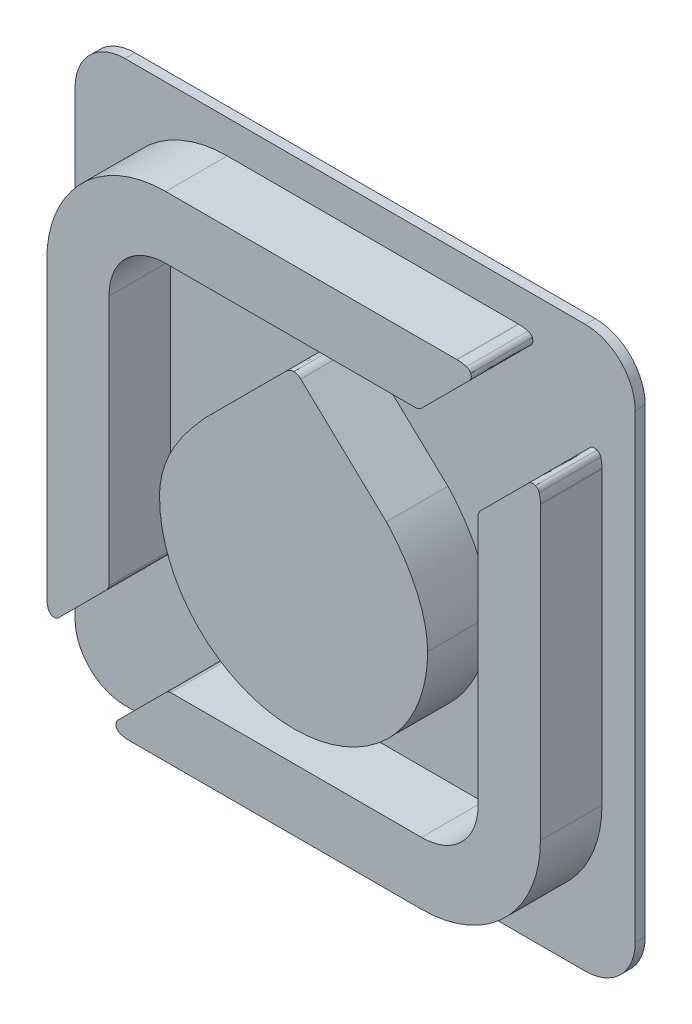
SolidWorks part; units mm, degrees
ref_plane "Front Plane" through (0, 0, 0) normal (0, 0, 1) x (1, 0, 0)
ref_plane "Top Plane" through (0, 0, 0) normal (0, 1, 0) x (1, 0, 0)
ref_plane "Right Plane" through (0, 0, 0) normal (1, 0, 0) x (0, 0, -1)
sketch "Sketch1" plane through (0, 0, 0) normal (0, 0, 1) x (1, 0, 0)
  line L0 (-0.4439, 10.3739) -> (-5.2973, 5.5207)
  line L1 (5.5576, 5.5207) -> (0.4078, 10.3739)
  line L2 (-7.7061, 12.3406) -> (7.3726, 12.3406)
  line L3 (7.6331, 12.4506) -> (10.56, 15.3777)
  line L4 (9.7814, 16.0818) -> (-7.7061, 16.0818)
  line L5 (-14.8551, 8.9323) -> (-14.8537, -8.5549)
  line L6 (-14.1496, -9.3319) -> (-11.224, -6.405)
  line L7 (-11.1125, -6.1461) -> (-11.1139, 8.9323)
  line L8 (7.67, -9.8545) -> (-7.4083, -9.8545)
  line L9 (-7.6688, -9.966) -> (-10.5958, -12.8929)
  line L10 (-9.8171, -13.5971) -> (7.67, -13.5971)
  line L11 (14.8194, -6.4463) -> (14.818, 11.0395)
  line L12 (14.1139, 11.8167) -> (11.1869, 8.8897)
  line L13 (11.0768, 8.6308) -> (11.0779, -6.4463)
  line L14 (-8.0765, 0) -> (8.0395, 0) construction
  line L15 (0, 10.5587) -> (0, -8.0393) construction
  spline S0 degree 3 poles (0, 10.5587) (-0.1504, 10.5587) (-0.3295, 10.487) (-0.4439, 10.3739) knots 0 0 0 0 1 1 1 1
  spline S1 degree 3 poles (-5.2973, 5.5207) (-5.3111, 5.508) (-5.3235, 5.4956) (-5.3344, 5.4832) knots 0 0 0 0 1 1 1 1
  spline S2 degree 3 poles (-5.3344, 5.4832) (-6.6213, 4.0569) (-8.0765, 2.26) (-8.0765, 0) knots 0 0 0 0 1 1 1 1
  spline S3 degree 3 poles (-8.0765, 0) (-8.0765, -4.44) (-4.4387, -8.0393) (0, -8.0393) knots 0 0 0 0 1 1 1 1
  spline S4 degree 3 poles (0, -8.0393) (4.4414, -8.0393) (8.0395, -4.44) (8.0395, 0) knots 0 0 0 0 1 1 1 1
  spline S5 degree 3 poles (8.0395, 0) (8.0395, 2.1015) (6.8156, 4.1908) (5.5576, 5.5207) knots 0 0 0 0 1 1 1 1
  spline S6 degree 3 poles (0.4078, 10.3739) (0.2949, 10.4829) (0.1545, 10.5587) (0, 10.5587) knots 0 0 0 0 1 1 1 1
  spline S7 degree 3 poles (7.3726, 12.3406) (7.44, 12.3472) (7.5049, 12.3734) (7.5585, 12.4136) knots 0 0 0 0 1 1 1 1
  spline S8 degree 3 poles (7.5585, 12.4136) (7.5847, 12.4245) (7.6094, 12.4354) (7.6331, 12.4506) knots 0 0 0 0 1 1 1 1
  spline S9 degree 3 poles (10.56, 15.3777) (10.6605, 15.4838) (10.691, 15.6504) (10.6331, 15.7854) knots 0 0 0 0 1 1 1 1
  spline S10 degree 3 poles (10.6331, 15.7854) (10.589, 15.8944) (10.4895, 15.9799) (10.3737, 16.0073) knots 0 0 0 0 1 1 1 1
  spline S11 degree 3 poles (10.3737, 16.0073) (10.1974, 16.0529) (10.0087, 16.0914) (9.8185, 16.0818) knots 0 0 0 0 1 1 1 1
  spline S12 degree 3 poles (9.8185, 16.0818) (9.8061, 16.0818) (9.7939, 16.0832) (9.7814, 16.0818) knots 0 0 0 0 1 1 1 1
  spline S13 degree 3 poles (-7.7061, 16.0818) (-11.6308, 16.0818) (-14.8551, 12.8585) (-14.8551, 8.9323) knots 0 0 0 0 1 1 1 1
  spline S14 degree 3 poles (-14.8537, -8.5549) (-14.8551, -8.5671) (-14.8537, -8.5781) (-14.8537, -8.5904) knots 0 0 0 0 1 1 1 1
  spline S15 degree 3 poles (-14.8537, -8.5904) (-14.8637, -8.782) (-14.8248, -8.9697) (-14.7807, -9.1476) knots 0 0 0 0 1 1 1 1
  spline S16 degree 3 poles (-14.7807, -9.1476) (-14.7518, -9.2618) (-14.6678, -9.3609) (-14.5577, -9.4064) knots 0 0 0 0 1 1 1 1
  spline S17 degree 3 poles (-14.5577, -9.4064) (-14.4241, -9.4642) (-14.2558, -9.4339) (-14.1496, -9.3319) knots 0 0 0 0 1 1 1 1
  spline S18 degree 3 poles (-11.224, -6.405) (-11.2088, -6.3817) (-11.1966, -6.3566) (-11.1869, -6.3306) knots 0 0 0 0 1 1 1 1
  spline S19 degree 3 poles (-11.1869, -6.3306) (-11.1457, -6.2784) (-11.1192, -6.2134) (-11.1125, -6.1461) knots 0 0 0 0 1 1 1 1
  spline S20 degree 3 poles (-11.1139, 8.9323) (-11.1139, 10.8565) (-9.6326, 12.3406) (-7.7061, 12.3406) knots 0 0 0 0 1 1 1 1
  spline S21 degree 3 poles (-7.4083, -9.8545) (-7.4757, -9.8626) (-7.5406, -9.8887) (-7.5942, -9.9285) knots 0 0 0 0 1 1 1 1
  spline S22 degree 3 poles (-7.5942, -9.9285) (-7.6204, -9.9384) (-7.6455, -9.9508) (-7.6688, -9.966) knots 0 0 0 0 1 1 1 1
  spline S23 degree 3 poles (-10.5958, -12.8929) (-10.6962, -12.9992) (-10.7267, -13.1656) (-10.6688, -13.3007) knots 0 0 0 0 1 1 1 1
  spline S24 degree 3 poles (-10.6688, -13.3007) (-10.6247, -13.4097) (-10.5241, -13.4951) (-10.4098, -13.5227) knots 0 0 0 0 1 1 1 1
  spline S25 degree 3 poles (-10.4098, -13.5227) (-10.2334, -13.5682) (-10.0447, -13.6066) (-9.8545, -13.5971) knots 0 0 0 0 1 1 1 1
  spline S26 degree 3 poles (-9.8545, -13.5971) (-9.8418, -13.5956) (-9.8296, -13.5971) (-9.8171, -13.5971) knots 0 0 0 0 1 1 1 1
  spline S27 degree 3 poles (7.67, -13.5971) (11.5947, -13.5971) (14.8209, -10.3724) (14.8194, -6.4463) knots 0 0 0 0 1 1 1 1
  spline S28 degree 3 poles (14.818, 11.0395) (14.8194, 11.0519) (14.818, 11.0643) (14.818, 11.0769) knots 0 0 0 0 1 1 1 1
  spline S29 degree 3 poles (14.818, 11.0769) (14.8276, 11.2671) (14.7891, 11.4558) (14.7436, 11.6321) knots 0 0 0 0 1 1 1 1
  spline S30 degree 3 poles (14.7436, 11.6321) (14.7161, 11.7465) (14.6308, 11.847) (14.5218, 11.8911) knots 0 0 0 0 1 1 1 1
  spline S31 degree 3 poles (14.5218, 11.8911) (14.3866, 11.949) (14.2201, 11.9186) (14.1139, 11.8167) knots 0 0 0 0 1 1 1 1
  spline S32 degree 3 poles (11.1869, 8.8897) (11.1718, 8.8678) (11.1593, 8.8418) (11.1499, 8.8167) knots 0 0 0 0 1 1 1 1
  spline S33 degree 3 poles (11.1499, 8.8167) (11.1096, 8.7631) (11.0836, 8.6982) (11.0768, 8.6308) knots 0 0 0 0 1 1 1 1
  spline S34 degree 3 poles (11.0779, -6.4463) (11.0793, -8.3713) (9.5965, -9.8545) (7.67, -9.8545) knots 0 0 0 0 1 1 1 1
extrude "Boss-Extrude1" add sketch "Sketch1" along normal blind 3.7
sketch "Sketch2" plane through (0, 0, 0) normal (0, 0, 1) x (1, 0, 0)
  line L0 (-14.8551, 8.9323) -> (-16.8551, 8.9323) construction
  line L1 (-16.8551, 18.0778) -> (16.8194, 18.0778)
  line L2 (-16.8551, 18.0778) -> (-16.8551, -15.5971)
  line L3 (-16.8551, -15.5971) -> (16.8194, -15.5971)
  line L4 (16.8194, 18.0778) -> (16.8194, -15.5971)
  line L5 (-7.9473, 16.0778) -> (-7.9473, 18.0778) construction
  line L6 (14.8194, -6.4463) -> (16.8194, -6.4463) construction
  line L7 (7.67, -13.5971) -> (7.67, -15.5971) construction
  spline S0 degree 3 poles (-7.7061, 16.0818) (-11.6308, 16.0818) (-14.8551, 12.8585) (-14.8551, 8.9323) knots 0 0 0 0 1 1 1 1 construction
  point P0 (0, 0)
  dimension "D1" = 2
extrude "Boss-Extrude2" add sketch "Sketch2" against normal blind 0.6
fillet "Fillet1" radius 3 4 edges at (-16.8551, -15.5971, -0.3) (16.8194, -15.5971, -0.3) (-16.8551, 18.0778, -0.3) (16.8194, 18.0778, -0.3)
sketch "Sketch3" plane through (0, 0, 0) normal (0, 0, 1) x (1, 0, 0)
  line L0 (-0.4439, 10.3744) -> (-5.2976, 5.521)
  line L1 (5.5579, 5.521) -> (0.4078, 10.3744)
  line L2 (-7.7065, 12.3412) -> (7.373, 12.3412)
  line L3 (7.6335, 12.4512) -> (10.5606, 15.3784)
  line L4 (9.7819, 16.0826) -> (-7.7065, 16.0826)
  line L5 (-14.8558, 8.9327) -> (-14.8545, -8.5553)
  line L6 (-14.1503, -9.3324) -> (-11.2245, -6.4053)
  line L7 (-11.113, -6.1464) -> (-11.1144, 8.9327)
  line L8 (7.6704, -9.855) -> (-7.4087, -9.855)
  line L9 (-7.6692, -9.9665) -> (-10.5963, -12.8936)
  line L10 (-9.8176, -13.5978) -> (7.6704, -13.5978)
  line L11 (14.8201, -6.4467) -> (14.8188, 11.04)
  line L12 (14.1146, 11.8173) -> (11.1874, 8.8902)
  line L13 (11.0773, 8.6312) -> (11.0784, -6.4467)
  line L14 (29.3977, 1.1866) -> (27.6725, 1.1866)
  line L15 (27.6725, 1.1866) -> (27.6725, 6.5529)
  line L16 (27.6725, -3.5649) -> (27.6725, 0.3487)
  line L17 (31.1507, -0.5676) -> (34.1272, -4.7585)
  line L18 (36.2856, -4.3009) -> (32.8307, 0.7829)
  line L19 (25.3049, 5.8184) -> (25.3049, -3.5649)
  line L20 (50.1342, 0.962) -> (43.1704, 0.8573)
  line L21 (43.0424, -0.1845) -> (52.5774, -0.1845)
  line L22 (59.4392, -3.0798) -> (59.4392, 0.9317)
  line L23 (57.2258, 2.3331) -> (57.2258, -9.36)
  line L24 (59.4392, -9.36) -> (59.4392, -5.4475)
  line L25 (77.8244, 1.1866) -> (76.0989, 1.1866)
  line L26 (76.0989, 1.1866) -> (76.0989, 6.5529)
  line L27 (76.0989, -3.5649) -> (76.0989, 0.3487)
  line L28 (79.5775, -0.5676) -> (82.5526, -4.7585)
  line L29 (84.712, -4.3009) -> (81.2557, 0.7829)
  line L30 (73.7313, 5.8184) -> (73.7313, -3.5649)
  line L31 (97.9983, -0.3128) -> (97.8247, -3.7166)
  line L32 (94.9473, -0.8972) -> (97.9983, -0.3128)
  line L33 (100.0367, -3.0798) -> (100.2103, 1.0143)
  line L34 (97.7958, 0.6022) -> (94.4912, 0.0456)
  line L35 (97.0323, -5.7481) -> (97.7436, -5.2673)
  line L36 (97.7436, -5.2673) -> (97.8247, -5.2673)
  line L37 (108.3507, -3.0798) -> (108.3507, 0.9317)
  line L38 (106.139, 2.3331) -> (106.139, -9.36)
  line L39 (108.3507, -9.36) -> (108.3507, -5.4475)
  line L40 (125.015, 1.0143) -> (125.015, 6.5529)
  line L41 (122.6527, 5.8184) -> (122.6527, -3.5649)
  line L42 (125.015, -3.5649) -> (125.015, 0.2205)
  line L43 (139.923, 2.6873) -> (139.923, -3.4615)
  line L44 (142.1337, -3.4615) -> (142.1337, 0.0456)
  spline S0 degree 3 poles (0, 10.5592) (-0.1504, 10.5592) (-0.3295, 10.4875) (-0.4439, 10.3744) knots 0 0 0 0 1 1 1 1
  spline S1 degree 3 poles (-5.2976, 5.521) (-5.3114, 5.5083) (-5.3237, 5.4959) (-5.3346, 5.4835) knots 0 0 0 0 1 1 1 1
  spline S2 degree 3 poles (-5.3346, 5.4835) (-6.6216, 4.0571) (-8.0769, 2.2601) (-8.0769, 0) knots 0 0 0 0 1 1 1 1
  spline S3 degree 3 poles (-8.0769, 0) (-8.0769, -4.4402) (-4.4389, -8.0397) (0, -8.0397) knots 0 0 0 0 1 1 1 1
  spline S4 degree 3 poles (0, -8.0397) (4.4416, -8.0397) (8.0399, -4.4402) (8.0399, 0) knots 0 0 0 0 1 1 1 1
  spline S5 degree 3 poles (8.0399, 0) (8.0399, 2.1016) (6.816, 4.191) (5.5579, 5.521) knots 0 0 0 0 1 1 1 1
  spline S6 degree 3 poles (0.4078, 10.3744) (0.2949, 10.4834) (0.1545, 10.5592) (0, 10.5592) knots 0 0 0 0 1 1 1 1
  spline S7 degree 3 poles (7.373, 12.3412) (7.4404, 12.3478) (7.5053, 12.374) (7.5589, 12.4143) knots 0 0 0 0 1 1 1 1
  spline S8 degree 3 poles (7.5589, 12.4143) (7.5851, 12.4251) (7.6098, 12.436) (7.6335, 12.4512) knots 0 0 0 0 1 1 1 1
  spline S9 degree 3 poles (10.5606, 15.3784) (10.661, 15.4845) (10.6915, 15.6511) (10.6336, 15.7862) knots 0 0 0 0 1 1 1 1
  spline S10 degree 3 poles (10.6336, 15.7862) (10.5895, 15.8952) (10.49, 15.9807) (10.3743, 16.0081) knots 0 0 0 0 1 1 1 1
  spline S11 degree 3 poles (10.3743, 16.0081) (10.1979, 16.0537) (10.0092, 16.0921) (9.819, 16.0826) knots 0 0 0 0 1 1 1 1
  spline S12 degree 3 poles (9.819, 16.0826) (9.8066, 16.0826) (9.7943, 16.084) (9.7819, 16.0826) knots 0 0 0 0 1 1 1 1
  spline S13 degree 3 poles (-7.7065, 16.0826) (-11.6314, 16.0826) (-14.8558, 12.8591) (-14.8558, 8.9327) knots 0 0 0 0 1 1 1 1
  spline S14 degree 3 poles (-14.8545, -8.5553) (-14.8558, -8.5676) (-14.8545, -8.5786) (-14.8545, -8.5908) knots 0 0 0 0 1 1 1 1
  spline S15 degree 3 poles (-14.8545, -8.5908) (-14.8644, -8.7824) (-14.8255, -8.9701) (-14.7814, -9.148) knots 0 0 0 0 1 1 1 1
  spline S16 degree 3 poles (-14.7814, -9.148) (-14.7525, -9.2622) (-14.6686, -9.3613) (-14.5584, -9.4068) knots 0 0 0 0 1 1 1 1
  spline S17 degree 3 poles (-14.5584, -9.4068) (-14.4248, -9.4647) (-14.2565, -9.4344) (-14.1503, -9.3324) knots 0 0 0 0 1 1 1 1
  spline S18 degree 3 poles (-11.2245, -6.4053) (-11.2094, -6.382) (-11.1971, -6.3569) (-11.1874, -6.3309) knots 0 0 0 0 1 1 1 1
  spline S19 degree 3 poles (-11.1874, -6.3309) (-11.1462, -6.2787) (-11.1198, -6.2137) (-11.113, -6.1464) knots 0 0 0 0 1 1 1 1
  spline S20 degree 3 poles (-11.1144, 8.9327) (-11.1144, 10.857) (-9.6331, 12.3412) (-7.7065, 12.3412) knots 0 0 0 0 1 1 1 1
  spline S21 degree 3 poles (-7.4087, -9.855) (-7.4761, -9.8631) (-7.541, -9.8892) (-7.5946, -9.929) knots 0 0 0 0 1 1 1 1
  spline S22 degree 3 poles (-7.5946, -9.929) (-7.6208, -9.9389) (-7.6459, -9.9513) (-7.6692, -9.9665) knots 0 0 0 0 1 1 1 1
  spline S23 degree 3 poles (-10.5963, -12.8936) (-10.6967, -12.9998) (-10.7272, -13.1663) (-10.6693, -13.3013) knots 0 0 0 0 1 1 1 1
  spline S24 degree 3 poles (-10.6693, -13.3013) (-10.6252, -13.4103) (-10.5246, -13.4958) (-10.4103, -13.5234) knots 0 0 0 0 1 1 1 1
  spline S25 degree 3 poles (-10.4103, -13.5234) (-10.2339, -13.5688) (-10.0452, -13.6073) (-9.855, -13.5978) knots 0 0 0 0 1 1 1 1
  spline S26 degree 3 poles (-9.855, -13.5978) (-9.8423, -13.5963) (-9.83, -13.5978) (-9.8176, -13.5978) knots 0 0 0 0 1 1 1 1
  spline S27 degree 3 poles (7.6704, -13.5978) (11.5952, -13.5978) (14.8217, -10.3729) (14.8201, -6.4467) knots 0 0 0 0 1 1 1 1
  spline S28 degree 3 poles (14.8188, 11.04) (14.8201, 11.0524) (14.8188, 11.0648) (14.8188, 11.0775) knots 0 0 0 0 1 1 1 1
  spline S29 degree 3 poles (14.8188, 11.0775) (14.8283, 11.2677) (14.7898, 11.4563) (14.7444, 11.6327) knots 0 0 0 0 1 1 1 1
  spline S30 degree 3 poles (14.7444, 11.6327) (14.7168, 11.7471) (14.6315, 11.8476) (14.5225, 11.8917) knots 0 0 0 0 1 1 1 1
  spline S31 degree 3 poles (14.5225, 11.8917) (14.3873, 11.9496) (14.2208, 11.9192) (14.1146, 11.8173) knots 0 0 0 0 1 1 1 1
  spline S32 degree 3 poles (11.1874, 8.8902) (11.1723, 8.8682) (11.1599, 8.8422) (11.1504, 8.8171) knots 0 0 0 0 1 1 1 1
  spline S33 degree 3 poles (11.1504, 8.8171) (11.1101, 8.7635) (11.0841, 8.6986) (11.0773, 8.6312) knots 0 0 0 0 1 1 1 1
  spline S34 degree 3 poles (11.0784, -6.4467) (11.0798, -8.3717) (9.597, -9.855) (7.6704, -9.855) knots 0 0 0 0 1 1 1 1
  spline S35 degree 3 poles (30.2881, 8.0304) (31.8397, 8.0304) (33.9247, 7.723) (33.9247, 4.8742) knots 0 0 0 0 1 1 1 1
  spline S36 degree 3 poles (33.9247, 4.8742) (33.9247, 1.8522) (31.8644, 1.1866) (29.3977, 1.1866) knots 0 0 0 0 1 1 1 1
  spline S37 degree 3 poles (27.6725, 6.5529) (27.6725, 7.2669) (28.4839, 8.0304) (30.2881, 8.0304) knots 0 0 0 0 1 1 1 1
  spline S38 degree 3 poles (27.6725, 0.3487) (29.8083, 0.3487) (30.7704, -0.0056) (31.1507, -0.5676) knots 0 0 0 0 1 1 1 1
  spline S39 degree 3 poles (34.1272, -4.7585) (34.8618, -5.8761) (35.9575, -6.918) (37.4844, -6.918) knots 0 0 0 0 1 1 1 1
  spline S40 degree 3 poles (37.4844, -6.918) (37.8676, -6.918) (38.2962, -6.871) (38.5513, -6.7443) knots 0 0 0 0 1 1 1 1
  spline S41 degree 3 poles (38.5513, -6.7443) (38.6243, -6.5636) (38.6243, -6.2565) (38.5262, -6.0553) knots 0 0 0 0 1 1 1 1
  spline S42 degree 3 poles (38.5262, -6.0553) (37.5314, -5.9795) (36.9471, -5.3427) (36.2856, -4.3009) knots 0 0 0 0 1 1 1 1
  spline S43 degree 3 poles (32.8307, 0.7829) (33.9247, 1.112) (36.4659, 2.3567) (36.4659, 4.8979) knots 0 0 0 0 1 1 1 1
  spline S44 degree 3 poles (36.4659, 4.8979) (36.4659, 6.1189) (36.0609, 7.1608) (35.1472, 7.9779) knots 0 0 0 0 1 1 1 1
  spline S45 degree 3 poles (35.1472, 7.9779) (33.9247, 9.0722) (31.8644, 9.0722) (30.2659, 9.0722) knots 0 0 0 0 1 1 1 1
  spline S46 degree 3 poles (30.2659, 9.0722) (29.6291, 9.0722) (27.4421, 8.9166) (26.4733, 8.9166) knots 0 0 0 0 1 1 1 1
  spline S47 degree 3 poles (26.4733, 8.9166) (25.5363, 8.9166) (24.292, 8.944) (23.1976, 8.9673) knots 0 0 0 0 1 1 1 1
  spline S48 degree 3 poles (23.1976, 8.9673) (23.0474, 8.8171) (23.0474, 8.1807) (23.1976, 8.029) knots 0 0 0 0 1 1 1 1
  spline S49 degree 3 poles (23.1976, 8.029) (24.9754, 7.9489) (25.3049, 7.8223) (25.3049, 5.8184) knots 0 0 0 0 1 1 1 1
  spline S50 degree 3 poles (25.3049, -3.5649) (25.3049, -5.576) (24.9754, -5.7011) (23.1976, -5.777) knots 0 0 0 0 1 1 1 1
  spline S51 degree 3 poles (23.1976, -5.777) (23.0474, -5.9288) (23.0474, -6.5636) (23.1976, -6.7154) knots 0 0 0 0 1 1 1 1
  spline S52 degree 3 poles (23.1976, -6.7154) (24.3139, -6.6907) (25.5363, -6.6631) (26.5037, -6.6631) knots 0 0 0 0 1 1 1 1
  spline S53 degree 3 poles (26.5037, -6.6631) (27.4696, -6.6631) (28.7143, -6.6907) (29.8842, -6.7154) knots 0 0 0 0 1 1 1 1
  spline S54 degree 3 poles (29.8842, -6.7154) (30.0345, -6.5636) (30.0345, -5.9288) (29.8842, -5.777) knots 0 0 0 0 1 1 1 1
  spline S55 degree 3 poles (29.8842, -5.777) (28.1008, -5.7011) (27.6725, -5.576) (27.6725, -3.5649) knots 0 0 0 0 1 1 1 1
  spline S56 degree 3 poles (43.1704, 0.8573) (43.755, 3.9083) (45.7642, 4.7713) (47.3916, 4.7713) knots 0 0 0 0 1 1 1 1
  spline S57 degree 3 poles (47.3916, 4.7713) (48.6126, 4.7713) (50.644, 4.0643) (50.644, 1.6222) knots 0 0 0 0 1 1 1 1
  spline S58 degree 3 poles (50.644, 1.6222) (50.644, 1.3671) (50.4923, 0.962) (50.1342, 0.962) knots 0 0 0 0 1 1 1 1
  spline S59 degree 3 poles (52.6299, -3.8959) (51.4308, -4.9899) (50.112, -5.6488) (48.2062, -5.6488) knots 0 0 0 0 1 1 1 1
  spline S60 degree 3 poles (48.2062, -5.6488) (46.5509, -5.6488) (45.0282, -5.088) (43.9864, -3.6175) knots 0 0 0 0 1 1 1 1
  spline S61 degree 3 poles (43.9864, -3.6175) (43.3496, -2.6516) (43.0424, -1.8645) (43.0424, -0.1845) knots 0 0 0 0 1 1 1 1
  spline S62 degree 3 poles (52.5774, -0.1845) (52.9372, -0.1845) (53.1852, 0.2494) (53.1852, 0.5554) knots 0 0 0 0 1 1 1 1
  spline S63 degree 3 poles (53.1852, 0.5554) (53.1852, 2.9424) (51.767, 5.788) (47.4428, 5.788) knots 0 0 0 0 1 1 1 1
  spline S64 degree 3 poles (47.4428, 5.788) (43.9353, 5.788) (40.6046, 3.3762) (40.6046, -0.9204) knots 0 0 0 0 1 1 1 1
  spline S65 degree 3 poles (40.6046, -0.9204) (40.6046, -2.4942) (41.139, -4.0461) (42.1812, -5.1169) knots 0 0 0 0 1 1 1 1
  spline S66 degree 3 poles (42.1812, -5.1169) (43.2519, -6.2565) (45.2089, -6.918) (47.4428, -6.918) knots 0 0 0 0 1 1 1 1
  spline S67 degree 3 poles (47.4428, -6.918) (49.8337, -6.918) (51.9409, -5.9288) (53.2141, -4.4525) knots 0 0 0 0 1 1 1 1
  spline S68 degree 3 poles (53.2141, -4.4525) (53.1397, -4.1728) (53.0131, -3.9177) (52.6299, -3.8959) knots 0 0 0 0 1 1 1 1
  spline S69 degree 3 poles (60.069, 2.536) (60.7812, 3.5252) (61.8756, 4.4925) (63.0222, 4.4925) knots 0 0 0 0 1 1 1 1
  spline S70 degree 3 poles (63.0222, 4.4925) (65.7895, 4.4925) (66.7844, 2.46) (66.7844, -0.7412) knots 0 0 0 0 1 1 1 1
  spline S71 degree 3 poles (66.7844, -0.7412) (66.7844, -3.9703) (65.2325, -5.8528) (62.6913, -5.8528) knots 0 0 0 0 1 1 1 1
  spline S72 degree 3 poles (62.6913, -5.8528) (61.4925, -5.8528) (59.6403, -4.5559) (59.4392, -3.0798) knots 0 0 0 0 1 1 1 1
  spline S73 degree 3 poles (59.4392, 0.9317) (59.4392, 1.5174) (59.7394, 2.1016) (60.069, 2.536) knots 0 0 0 0 1 1 1 1
  spline S74 degree 3 poles (59.4392, 3.5252) (59.4392, 4.3658) (59.4089, 5.3555) (59.2819, 5.6628) knots 0 0 0 0 1 1 1 1
  spline S75 degree 3 poles (59.2819, 5.6628) (59.2349, 5.7894) (59.1841, 5.8941) (58.9513, 5.8941) knots 0 0 0 0 1 1 1 1
  spline S76 degree 3 poles (58.9513, 5.8941) (58.1642, 5.587) (57.019, 5.3086) (55.0607, 5.0535) knots 0 0 0 0 1 1 1 1
  spline S77 degree 3 poles (55.0607, 5.0535) (55.0155, 4.8742) (55.0896, 4.4404) (55.1422, 4.2667) knots 0 0 0 0 1 1 1 1
  spline S78 degree 3 poles (55.1422, 4.2667) (56.6648, 4.1107) (57.2258, 3.9841) (57.2258, 2.3331) knots 0 0 0 0 1 1 1 1
  spline S79 degree 3 poles (57.2258, -9.36) (57.2258, -11.4672) (56.6885, -11.5952) (55.1422, -11.6768) knots 0 0 0 0 1 1 1 1
  spline S80 degree 3 poles (55.1422, -11.6768) (54.9862, -11.8268) (54.9862, -12.4635) (55.1422, -12.6152) knots 0 0 0 0 1 1 1 1
  spline S81 degree 3 poles (55.1422, -12.6152) (56.2073, -12.5916) (57.0702, -12.5612) (58.3434, -12.5612) knots 0 0 0 0 1 1 1 1
  spline S82 degree 3 poles (58.3434, -12.5612) (59.767, -12.5612) (60.9372, -12.5916) (62.0326, -12.6152) knots 0 0 0 0 1 1 1 1
  spline S83 degree 3 poles (62.0326, -12.6152) (62.1815, -12.4635) (62.1815, -11.8268) (62.0326, -11.6768) knots 0 0 0 0 1 1 1 1
  spline S84 degree 3 poles (62.0326, -11.6768) (59.7162, -11.572) (59.4392, -11.4672) (59.4392, -9.36) knots 0 0 0 0 1 1 1 1
  spline S85 degree 3 poles (59.4392, -5.4475) (60.2482, -6.3322) (61.3658, -6.918) (62.8652, -6.918) knots 0 0 0 0 1 1 1 1
  spline S86 degree 3 poles (62.8652, -6.918) (64.4443, -6.918) (65.9162, -6.437) (67.086, -5.3427) knots 0 0 0 0 1 1 1 1
  spline S87 degree 3 poles (67.086, -5.3427) (68.4104, -4.0461) (69.2208, -2.2685) (69.2208, 0.0181) knots 0 0 0 0 1 1 1 1
  spline S88 degree 3 poles (69.2208, 0.0181) (69.2208, 3.4797) (67.3923, 5.7894) (63.8848, 5.7894) knots 0 0 0 0 1 1 1 1
  spline S89 degree 3 poles (63.8848, 5.7894) (61.9264, 5.7894) (60.758, 4.8524) (59.6636, 3.4275) knots 0 0 0 0 1 1 1 1
  spline S90 degree 3 poles (59.6636, 3.4275) (59.5645, 3.3226) (59.4392, 3.3226) (59.4392, 3.5252) knots 0 0 0 0 1 1 1 1
  spline S91 degree 3 poles (78.7145, 8.0304) (80.2665, 8.0304) (82.3501, 7.723) (82.3501, 4.8742) knots 0 0 0 0 1 1 1 1
  spline S92 degree 3 poles (82.3501, 4.8742) (82.3501, 1.8522) (80.2898, 1.1866) (77.8244, 1.1866) knots 0 0 0 0 1 1 1 1
  spline S93 degree 3 poles (76.0989, 6.5529) (76.0989, 7.2669) (76.9093, 8.0304) (78.7145, 8.0304) knots 0 0 0 0 1 1 1 1
  spline S94 degree 3 poles (76.0989, 0.3487) (78.2351, 0.3487) (79.201, -0.0056) (79.5775, -0.5676) knots 0 0 0 0 1 1 1 1
  spline S95 degree 3 poles (82.5526, -4.7585) (83.2942, -5.8761) (84.3843, -6.918) (85.9112, -6.918) knots 0 0 0 0 1 1 1 1
  spline S96 degree 3 poles (85.9112, -6.918) (86.2943, -6.918) (86.7226, -6.871) (86.9763, -6.7443) knots 0 0 0 0 1 1 1 1
  spline S97 degree 3 poles (86.9763, -6.7443) (87.0507, -6.5636) (87.0507, -6.2565) (86.953, -6.0553) knots 0 0 0 0 1 1 1 1
  spline S98 degree 3 poles (86.953, -6.0553) (85.9634, -5.9795) (85.3778, -5.3427) (84.712, -4.3009) knots 0 0 0 0 1 1 1 1
  spline S99 degree 3 poles (81.2557, 0.7829) (82.3501, 1.112) (84.8913, 2.3567) (84.8913, 4.8979) knots 0 0 0 0 1 1 1 1
  spline S100 degree 3 poles (84.8913, 4.8979) (84.8913, 6.1189) (84.4877, 7.1608) (83.5725, 7.9779) knots 0 0 0 0 1 1 1 1
  spline S101 degree 3 poles (83.5725, 7.9779) (82.3501, 9.0722) (80.2898, 9.0722) (78.6927, 9.0722) knots 0 0 0 0 1 1 1 1
  spline S102 degree 3 poles (78.6927, 9.0722) (78.0559, 9.0722) (75.8661, 8.9166) (74.9001, 8.9166) knots 0 0 0 0 1 1 1 1
  spline S103 degree 3 poles (74.9001, 8.9166) (73.9617, 8.9166) (72.717, 8.944) (71.623, 8.9673) knots 0 0 0 0 1 1 1 1
  spline S104 degree 3 poles (71.623, 8.9673) (71.4741, 8.8171) (71.4741, 8.1807) (71.623, 8.029) knots 0 0 0 0 1 1 1 1
  spline S105 degree 3 poles (71.623, 8.029) (73.4007, 7.9489) (73.7313, 7.8223) (73.7313, 5.8184) knots 0 0 0 0 1 1 1 1
  spline S106 degree 3 poles (73.7313, -3.5649) (73.7313, -5.576) (73.4007, -5.7011) (71.623, -5.777) knots 0 0 0 0 1 1 1 1
  spline S107 degree 3 poles (71.623, -5.777) (71.4741, -5.9288) (71.4741, -6.5636) (71.623, -6.7154) knots 0 0 0 0 1 1 1 1
  spline S108 degree 3 poles (71.623, -6.7154) (72.7406, -6.6907) (73.9617, -6.6631) (74.9304, -6.6631) knots 0 0 0 0 1 1 1 1
  spline S109 degree 3 poles (74.9304, -6.6631) (75.8964, -6.6631) (77.1407, -6.6907) (78.3109, -6.7154) knots 0 0 0 0 1 1 1 1
  spline S110 degree 3 poles (78.3109, -6.7154) (78.4598, -6.5636) (78.4598, -5.9288) (78.3109, -5.777) knots 0 0 0 0 1 1 1 1
  spline S111 degree 3 poles (78.3109, -5.777) (76.5275, -5.7011) (76.0989, -5.576) (76.0989, -3.5649) knots 0 0 0 0 1 1 1 1
  spline S112 degree 3 poles (97.8247, -3.7166) (97.7958, -4.1221) (97.57, -4.3299) (97.3149, -4.5038) knots 0 0 0 0 1 1 1 1
  spline S113 degree 3 poles (97.3149, -4.5038) (96.4467, -5.0658) (94.9018, -5.777) (93.9577, -5.777) knots 0 0 0 0 1 1 1 1
  spline S114 degree 3 poles (93.9577, -5.777) (92.2559, -5.777) (91.6191, -4.6827) (91.6191, -3.82) knots 0 0 0 0 1 1 1 1
  spline S115 degree 3 poles (91.6191, -3.82) (91.6191, -2.3965) (92.7879, -1.3244) (94.9473, -0.8972) knots 0 0 0 0 1 1 1 1
  spline S116 degree 3 poles (97.8247, -5.2673) (97.9531, -6.1298) (98.2534, -6.918) (100.0064, -6.918) knots 0 0 0 0 1 1 1 1
  spline S117 degree 3 poles (100.0064, -6.918) (101.9411, -6.918) (103.0066, -5.8293) (103.0066, -5.5219) knots 0 0 0 0 1 1 1 1
  spline S118 degree 3 poles (103.0066, -5.5219) (103.0066, -5.3209) (102.7282, -5.0355) (102.5779, -5.0355) knots 0 0 0 0 1 1 1 1
  spline S119 degree 3 poles (102.5779, -5.0355) (102.3754, -5.0355) (102.2721, -5.5) (101.5816, -5.5) knots 0 0 0 0 1 1 1 1
  spline S120 degree 3 poles (101.5816, -5.5) (100.3151, -5.5) (99.9553, -4.352) (100.0367, -3.0798) knots 0 0 0 0 1 1 1 1
  spline S121 degree 3 poles (100.2103, 1.0143) (100.4403, 5.0013) (97.9228, 5.7894) (95.533, 5.7894) knots 0 0 0 0 1 1 1 1
  spline S122 degree 3 poles (95.533, 5.7894) (92.8637, 5.7894) (90.0964, 4.1853) (90.0964, 2.664) knots 0 0 0 0 1 1 1 1
  spline S123 degree 3 poles (90.0964, 2.664) (90.0964, 1.9736) (90.5773, 1.673) (91.2373, 1.673) knots 0 0 0 0 1 1 1 1
  spline S124 degree 3 poles (91.2373, 1.673) (92.0244, 1.673) (92.6376, 2.1306) (92.6376, 2.4834) knots 0 0 0 0 1 1 1 1
  spline S125 degree 3 poles (92.6376, 2.4834) (92.6376, 2.6873) (92.5868, 2.9177) (92.5342, 3.022) knots 0 0 0 0 1 1 1 1
  spline S126 degree 3 poles (92.5342, 3.022) (92.5109, 3.098) (92.482, 3.2705) (92.482, 3.5777) knots 0 0 0 0 1 1 1 1
  spline S127 degree 3 poles (92.482, 3.5777) (92.482, 4.4692) (94.0322, 4.7713) (95.2835, 4.7713) knots 0 0 0 0 1 1 1 1
  spline S128 degree 3 poles (95.2835, 4.7713) (96.6563, 4.7713) (98.0509, 4.0643) (98.0509, 0.962) knots 0 0 0 0 1 1 1 1
  spline S129 degree 3 poles (98.0509, 0.962) (98.0509, 0.7592) (97.8716, 0.6312) (97.7958, 0.6022) knots 0 0 0 0 1 1 1 1
  spline S130 degree 3 poles (94.4912, 0.0456) (90.8556, -0.5898) (89.1015, -2.0655) (89.1015, -3.9481) knots 0 0 0 0 1 1 1 1
  spline S131 degree 3 poles (89.1015, -3.9481) (89.1015, -6.1075) (90.8556, -6.918) (93.1943, -6.918) knots 0 0 0 0 1 1 1 1
  spline S132 degree 3 poles (93.1943, -6.918) (94.7462, -6.918) (95.533, -6.6907) (97.0323, -5.7481) knots 0 0 0 0 1 1 1 1
  spline S133 degree 3 poles (108.9875, 2.536) (109.6945, 3.5252) (110.7885, 4.4925) (111.9337, 4.4925) knots 0 0 0 0 1 1 1 1
  spline S134 degree 3 poles (111.9337, 4.4925) (114.7067, 4.4925) (115.6963, 2.46) (115.6963, -0.7412) knots 0 0 0 0 1 1 1 1
  spline S135 degree 3 poles (115.6963, -0.7412) (115.6963, -3.9703) (114.1457, -5.8528) (111.6045, -5.8528) knots 0 0 0 0 1 1 1 1
  spline S136 degree 3 poles (111.6045, -5.8528) (110.4054, -5.8528) (108.5532, -4.5559) (108.3507, -3.0798) knots 0 0 0 0 1 1 1 1
  spline S137 degree 3 poles (108.3507, 0.9317) (108.3507, 1.5174) (108.6527, 2.1016) (108.9875, 2.536) knots 0 0 0 0 1 1 1 1
  spline S138 degree 3 poles (108.3507, 3.5252) (108.3507, 4.3658) (108.3218, 5.3555) (108.1951, 5.6628) knots 0 0 0 0 1 1 1 1
  spline S139 degree 3 poles (108.1951, 5.6628) (108.1482, 5.7894) (108.0971, 5.8941) (107.8642, 5.8941) knots 0 0 0 0 1 1 1 1
  spline S140 degree 3 poles (107.8642, 5.8941) (107.0775, 5.587) (105.9362, 5.3086) (103.9739, 5.0535) knots 0 0 0 0 1 1 1 1
  spline S141 degree 3 poles (103.9739, 5.0535) (103.9284, 4.8742) (104.0029, 4.4404) (104.0551, 4.2667) knots 0 0 0 0 1 1 1 1
  spline S142 degree 3 poles (104.0551, 4.2667) (105.5781, 4.1107) (106.139, 3.9841) (106.139, 2.3331) knots 0 0 0 0 1 1 1 1
  spline S143 degree 3 poles (106.139, -9.36) (106.139, -11.4672) (105.6014, -11.5952) (104.0551, -11.6768) knots 0 0 0 0 1 1 1 1
  spline S144 degree 3 poles (104.0551, -11.6768) (103.8995, -11.8268) (103.8995, -12.4635) (104.0551, -12.6152) knots 0 0 0 0 1 1 1 1
  spline S145 degree 3 poles (104.0551, -12.6152) (105.1205, -12.5916) (105.9831, -12.5612) (107.2567, -12.5612) knots 0 0 0 0 1 1 1 1
  spline S146 degree 3 poles (107.2567, -12.5612) (108.6802, -12.5612) (109.8501, -12.5916) (110.9445, -12.6152) knots 0 0 0 0 1 1 1 1
  spline S147 degree 3 poles (110.9445, -12.6152) (111.0948, -12.4635) (111.0948, -11.8268) (110.9445, -11.6768) knots 0 0 0 0 1 1 1 1
  spline S148 degree 3 poles (110.9445, -11.6768) (108.6291, -11.572) (108.3507, -11.4672) (108.3507, -9.36) knots 0 0 0 0 1 1 1 1
  spline S149 degree 3 poles (108.3507, -5.4475) (109.1611, -6.3322) (110.2787, -6.918) (111.7838, -6.918) knots 0 0 0 0 1 1 1 1
  spline S150 degree 3 poles (111.7838, -6.918) (113.3576, -6.918) (114.828, -6.437) (115.9993, -5.3427) knots 0 0 0 0 1 1 1 1
  spline S151 degree 3 poles (115.9993, -5.3427) (117.3237, -4.0461) (118.1341, -2.2685) (118.1341, 0.0181) knots 0 0 0 0 1 1 1 1
  spline S152 degree 3 poles (118.1341, 0.0181) (118.1341, 3.4797) (116.3052, 5.7894) (112.7966, 5.7894) knots 0 0 0 0 1 1 1 1
  spline S153 degree 3 poles (112.7966, 5.7894) (110.8397, 5.7894) (109.6709, 4.8524) (108.5769, 3.4275) knots 0 0 0 0 1 1 1 1
  spline S154 degree 3 poles (108.5769, 3.4275) (108.4777, 3.3226) (108.3507, 3.3226) (108.3507, 3.5252) knots 0 0 0 0 1 1 1 1
  spline S155 degree 3 poles (125.015, 6.5529) (125.015, 7.4462) (125.7495, 8.0536) (127.7876, 8.0536) knots 0 0 0 0 1 1 1 1
  spline S156 degree 3 poles (127.7876, 8.0536) (129.6165, 8.0536) (131.3184, 7.6473) (131.3184, 4.5669) knots 0 0 0 0 1 1 1 1
  spline S157 degree 3 poles (131.3184, 4.5669) (131.3184, 1.9514) (130.3288, 0.8573) (127.578, 0.8573) knots 0 0 0 0 1 1 1 1
  spline S158 degree 3 poles (127.578, 0.8573) (126.8725, 0.8573) (125.2919, 0.9332) (125.015, 1.0143) knots 0 0 0 0 1 1 1 1
  spline S159 degree 3 poles (122.6527, -3.5649) (122.6527, -5.576) (121.9637, -5.7011) (120.1859, -5.777) knots 0 0 0 0 1 1 1 1
  spline S160 degree 3 poles (120.1859, -5.777) (120.0289, -5.9288) (120.0289, -6.5636) (120.1859, -6.7154) knots 0 0 0 0 1 1 1 1
  spline S161 degree 3 poles (120.1859, -6.7154) (121.4302, -6.6907) (122.7507, -6.6631) (123.9495, -6.6631) knots 0 0 0 0 1 1 1 1
  spline S162 degree 3 poles (123.9495, -6.6631) (124.9391, -6.6631) (126.8435, -6.6907) (128.1171, -6.7154) knots 0 0 0 0 1 1 1 1
  spline S163 degree 3 poles (128.1171, -6.7154) (128.2671, -6.5636) (128.2671, -5.9288) (128.1171, -5.777) knots 0 0 0 0 1 1 1 1
  spline S164 degree 3 poles (128.1171, -5.777) (126.1326, -5.6736) (125.015, -5.576) (125.015, -3.5649) knots 0 0 0 0 1 1 1 1
  spline S165 degree 3 poles (125.015, 0.2205) (125.5745, 0.0456) (126.7155, -0.11) (127.7061, -0.11) knots 0 0 0 0 1 1 1 1
  spline S166 degree 3 poles (127.7061, -0.11) (132.841, -0.11) (133.8828, 2.8142) (133.8828, 5.0013) knots 0 0 0 0 1 1 1 1
  spline S167 degree 3 poles (133.8828, 5.0013) (133.8828, 6.4262) (132.968, 9.0722) (127.9887, 9.0722) knots 0 0 0 0 1 1 1 1
  spline S168 degree 3 poles (127.9887, 9.0722) (127.2475, 9.0722) (124.9391, 8.9166) (123.9192, 8.9166) knots 0 0 0 0 1 1 1 1
  spline S169 degree 3 poles (123.9192, 8.9166) (122.8252, 8.9166) (121.6109, 8.944) (120.441, 8.9673) knots 0 0 0 0 1 1 1 1
  spline S170 degree 3 poles (120.441, 8.9673) (120.2837, 8.8171) (120.2837, 8.1807) (120.441, 8.029) knots 0 0 0 0 1 1 1 1
  spline S171 degree 3 poles (120.441, 8.029) (122.2187, 7.9489) (122.6527, 7.8223) (122.6527, 5.8184) knots 0 0 0 0 1 1 1 1
  spline S172 degree 3 poles (142.1337, 3.6536) (142.1337, 5.026) (142.0606, 5.4077) (141.9326, 5.6628) knots 0 0 0 0 1 1 1 1
  spline S173 degree 3 poles (141.9326, 5.6628) (141.8786, 5.7894) (141.8331, 5.8638) (141.6253, 5.8638) knots 0 0 0 0 1 1 1 1
  spline S174 degree 3 poles (141.6253, 5.8638) (140.5076, 5.6628) (138.5284, 5.3555) (136.7729, 5.1293) knots 0 0 0 0 1 1 1 1
  spline S175 degree 3 poles (136.7729, 5.1293) (136.7218, 4.9791) (136.7729, 4.5669) (136.8252, 4.4185) knots 0 0 0 0 1 1 1 1
  spline S176 degree 3 poles (136.8252, 4.4185) (137.4108, 4.4185) (139.263, 4.2141) (139.518, 4.0643) knots 0 0 0 0 1 1 1 1
  spline S177 degree 3 poles (139.518, 4.0643) (139.8475, 3.8561) (139.923, 3.5252) (139.923, 2.6873) knots 0 0 0 0 1 1 1 1
  spline S178 degree 3 poles (139.923, -3.4615) (139.923, -4.6827) (139.795, -5.1638) (139.4422, -5.4186) knots 0 0 0 0 1 1 1 1
  spline S179 degree 3 poles (139.4422, -5.4186) (139.1871, -5.5977) (137.1271, -5.7244) (136.085, -5.777) knots 0 0 0 0 1 1 1 1
  spline S180 degree 3 poles (136.085, -5.777) (135.9351, -5.9288) (135.9351, -6.5636) (136.085, -6.7154) knots 0 0 0 0 1 1 1 1
  spline S181 degree 3 poles (136.085, -6.7154) (137.1561, -6.6907) (140.3298, -6.6631) (141.3469, -6.6631) knots 0 0 0 0 1 1 1 1
  spline S182 degree 3 poles (141.3469, -6.6631) (142.3887, -6.6631) (145.4923, -6.6907) (146.5863, -6.7154) knots 0 0 0 0 1 1 1 1
  spline S183 degree 3 poles (146.5863, -6.7154) (146.738, -6.5636) (146.738, -5.9288) (146.5863, -5.777) knots 0 0 0 0 1 1 1 1
  spline S184 degree 3 poles (146.5863, -5.777) (145.6962, -5.7481) (143.0033, -5.576) (142.696, -5.4186) knots 0 0 0 0 1 1 1 1
  spline S185 degree 3 poles (142.696, -5.4186) (142.2398, -5.1638) (142.1337, -4.7063) (142.1337, -3.4615) knots 0 0 0 0 1 1 1 1
  spline S186 degree 3 poles (142.1337, 0.0456) (142.1337, 0.7071) (142.3665, 1.2391) (142.7482, 1.673) knots 0 0 0 0 1 1 1 1
  spline S187 degree 3 poles (142.7482, 1.673) (144.1718, 3.2482) (145.4164, 4.29) (146.4071, 4.29) knots 0 0 0 0 1 1 1 1
  spline S188 degree 3 poles (146.4071, 4.29) (146.7599, 4.29) (147.3444, 3.9841) (147.5247, 3.7803) knots 0 0 0 0 1 1 1 1
  spline S189 degree 3 poles (147.5247, 3.7803) (147.8031, 3.4797) (148.1834, 3.098) (148.6935, 3.098) knots 0 0 0 0 1 1 1 1
  spline S190 degree 3 poles (148.6935, 3.098) (149.3536, 3.098) (149.8923, 3.8106) (149.8923, 4.4925) knots 0 0 0 0 1 1 1 1
  spline S191 degree 3 poles (149.8923, 4.4925) (149.8923, 5.0013) (149.585, 5.7894) (148.4385, 5.7894) knots 0 0 0 0 1 1 1 1
  spline S192 degree 3 poles (148.4385, 5.7894) (145.3653, 5.7894) (144.092, 4.6195) (142.3887, 2.8432) knots 0 0 0 0 1 1 1 1
  spline S193 degree 3 poles (142.3887, 2.8432) (142.164, 2.5882) (142.1337, 2.8142) (142.1337, 3.6536) knots 0 0 0 0 1 1 1 1
  spline S194 degree 3 poles (151.5558, -0.8212) (151.5558, -3.7166) (153.6919, -6.918) (158.1375, -6.918) knots 0 0 0 0 1 1 1 1
  spline S195 degree 3 poles (158.1375, -6.918) (160.147, -6.918) (161.6753, -6.2868) (162.7404, -5.3427) knots 0 0 0 0 1 1 1 1
  spline S196 degree 3 poles (162.7404, -5.3427) (164.1639, -4.097) (164.7718, -2.2932) (164.7718, -0.5676) knots 0 0 0 0 1 1 1 1
  spline S197 degree 3 poles (164.7718, -0.5676) (164.7718, 2.3856) (162.9718, 5.7894) (158.1887, 5.7894) knots 0 0 0 0 1 1 1 1
  spline S198 degree 3 poles (158.1887, 5.7894) (156.1297, 5.7894) (154.4568, 5.026) (153.3088, 3.8106) knots 0 0 0 0 1 1 1 1
  spline S199 degree 3 poles (153.3088, 3.8106) (152.1925, 2.5882) (151.5558, 0.962) (151.5558, -0.8212) knots 0 0 0 0 1 1 1 1
  spline S200 degree 3 poles (157.6813, 4.7476) (160.581, 4.7476) (162.334, 2.664) (162.334, -1.505) knots 0 0 0 0 1 1 1 1
  spline S201 degree 3 poles (162.334, -1.505) (162.334, -5.1416) (160.1992, -5.8761) (158.5951, -5.8761) knots 0 0 0 0 1 1 1 1
  spline S202 degree 3 poles (158.5951, -5.8761) (155.1155, -5.8761) (153.9978, -2.4198) (153.9978, -0.1845) knots 0 0 0 0 1 1 1 1
  spline S203 degree 3 poles (153.9978, -0.1845) (153.9978, 2.3331) (154.7101, 4.7476) (157.6813, 4.7476) knots 0 0 0 0 1 1 1 1
